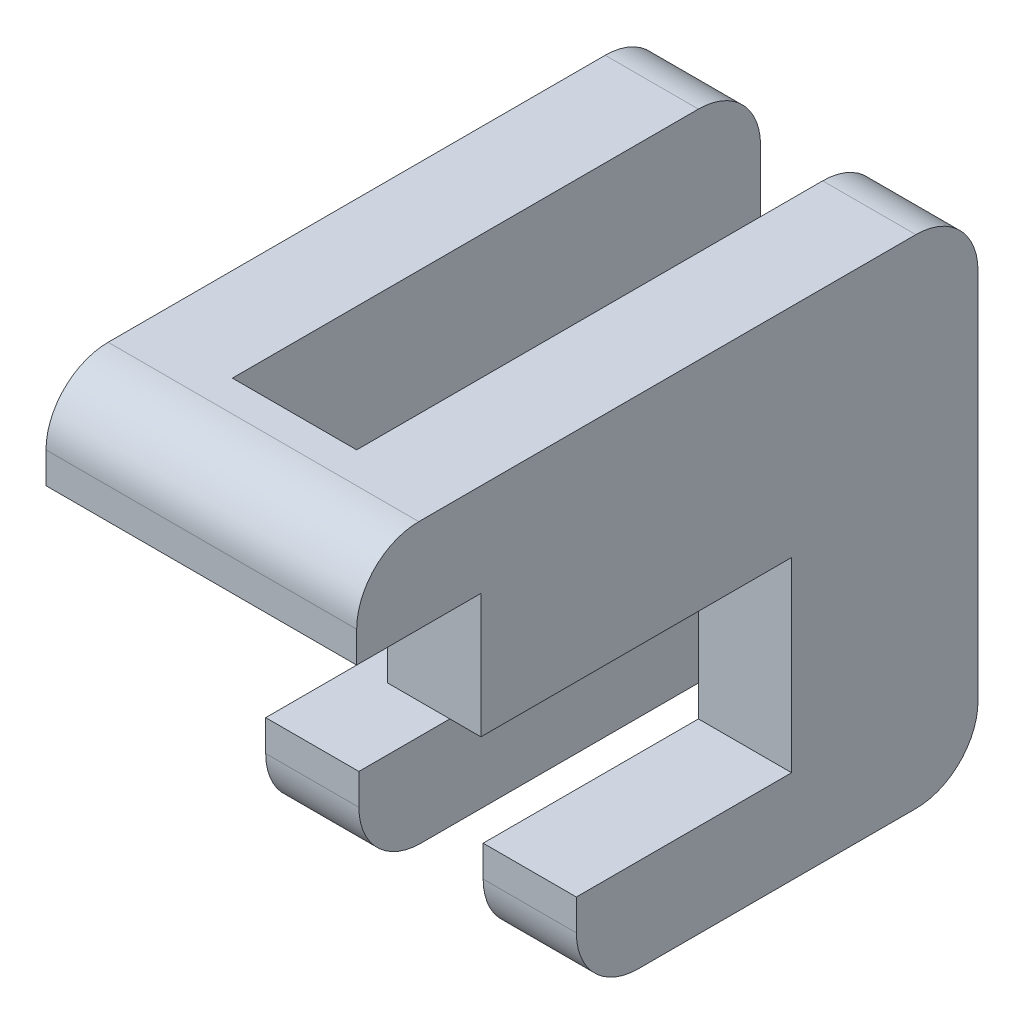
SolidWorks part; units mm, degrees
ref_plane "前视基准面" through (0, 0, 0) normal (0, 0, 1) x (1, 0, 0)
ref_plane "上视基准面" through (0, 0, 0) normal (0, 1, 0) x (1, 0, 0)
ref_plane "右视基准面" through (0, 0, 0) normal (1, 0, 0) x (0, 0, -1)
other "Configuration Table"
sketch "草图1" plane through (0, 0, 0) normal (1, 0, 0) x (0, 0, -1)
  line L9 (2, 0) -> (18, 0)
  line L10 (20, -2) -> (20, -14)
  line L11 (18, -16) -> (9.0715, -16)
  line L12 (7.0715, -14) -> (7.0715, -13)
  line L13 (7.0715, -13) -> (14, -13)
  line L14 (14, -13) -> (14, -7)
  line L15 (14, -7) -> (4, -7)
  line L16 (4, -7) -> (4, -3)
  line L17 (4, -3) -> (0, -3)
  line L18 (0, -3) -> (0, -2)
  arc A5 (2, 0) -> (0, -2) centre (2, -2) ccw
  arc A6 (9.0715, -16) -> (7.0715, -14) centre (9.0715, -14) cw
  arc A7 (20, -14) -> (18, -16) centre (18, -14) cw
  arc A8 (18, 0) -> (20, -2) centre (18, -2) cw
  point P13 (0, 0)
  point P16 (7.0715, -16)
  point P21 (20, 0)
  dimension "D5" = 20
  dimension "D8" = 2
  dimension "D1" = 6
  dimension "D2" = 4
  dimension "D3" = 3
  dimension "D4" = 3
  dimension "D6" = 4
  dimension "D7" = 10
extrude "凸台-拉伸1" add sketch "草图1" along normal blind 10
sketch "草图2" plane through (0, 0, 0) normal (0, 1, 0) x (1, 0, 0)
  line L1 (10, 20) -> (0, 20) construction
  line L2 (3, 3) -> (7, 3)
  line L3 (7, 3) -> (7, 20)
  line L4 (7, 20) -> (3, 20)
  line L5 (3, 3) -> (3, 20)
  dimension "D2" = 17
extrude "切除-拉伸1" cut sketch "草图2" against normal through all
